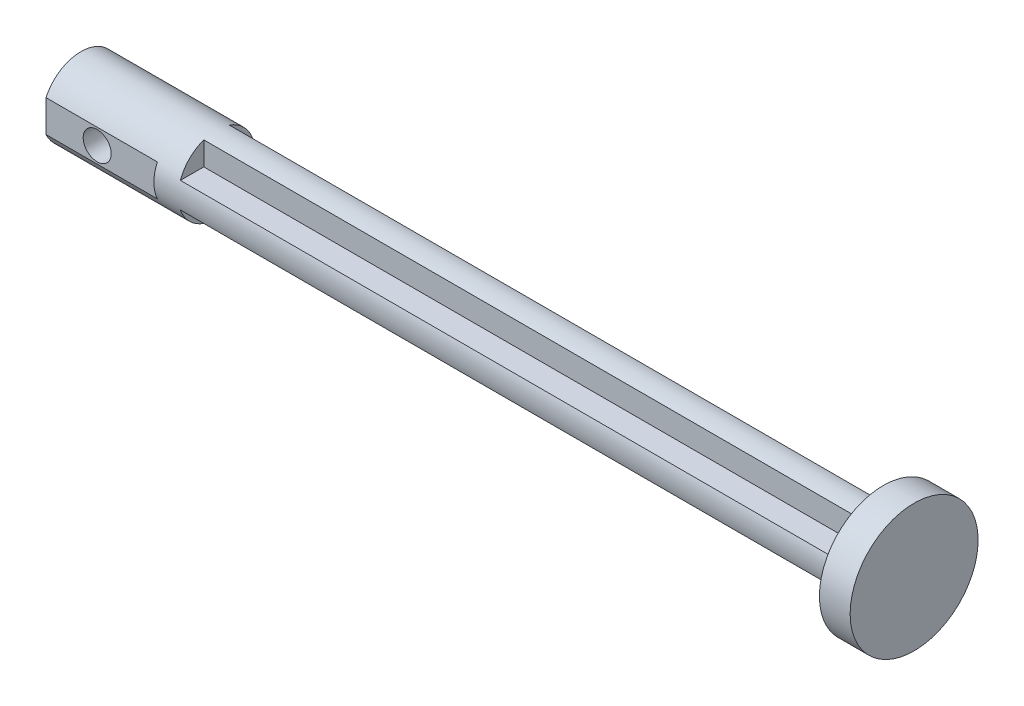
SolidWorks part; units mm, degrees
ref_plane "Front" through (0, 0, 0) normal (0, 0, 1) x (1, 0, 0)
ref_plane "Top" through (0, 0, 0) normal (0, 1, 0) x (1, 0, 0)
ref_plane "Right" through (0, 0, 0) normal (1, 0, 0) x (0, 0, -1)
sketch "Sketch1" plane through (0, 0, 0) normal (1, 0, 0) x (0, 0, -1)
  circle A0 centre (0, 0) radius 3.81
  dimension "D1" = 7.62
extrude "Base-Extrude" add sketch "Sketch1" along normal blind 13.462
ref_plane "Plane5" through (79.629, 0, 0) normal (1, 0, 0) x (0, 0, -1)
sketch "Sketch2" plane through (13.462, 0, 0) normal (1, 0, 0) x (0, 0, -1)
  line L0 (1.27, -1.27) -> (-1.27, 1.27) construction
  line L1 (1.27, -3.5921) -> (1.27, -1.27)
  line L2 (1.27, 1.27) -> (-1.27, -1.27) construction
  line L3 (-1.27, 3.5921) -> (-1.27, 1.27)
  line L4 (3.5921, 1.27) -> (1.27, 1.27)
  line L6 (-3.5921, -1.27) -> (-1.27, -1.27)
  line L8 (-1.27, 1.27) -> (-3.5921, 1.27)
  line L9 (1.27, 1.27) -> (1.27, 3.5921)
  line L10 (-1.27, -1.27) -> (-1.27, -3.5921)
  line L11 (1.27, -1.27) -> (3.5921, -1.27)
  circle A0 centre (0, 0) radius 3.81 construction
  arc A1 (1.27, 3.5921) -> (-1.27, 3.5921) centre (0, 0) ccw
  arc A2 (-3.5921, 1.27) -> (-3.5921, -1.27) centre (0, 0) ccw
  arc A3 (-1.27, -3.5921) -> (1.27, -3.5921) centre (0, 0) ccw
  arc A4 (3.5921, -1.27) -> (3.5921, 1.27) centre (0, 0) ccw
  dimension "D1" = 2.54
extrude "Boss-Extrude4" add sketch "Sketch2" along normal up to surface (66.167 mm away) up to plane "Plane5"
sketch "Sketch3" plane through (79.629, 0, 0) normal (1, 0, 0) x (0, 0, -1)
  circle A0 centre (0, 0) radius 6.35
  dimension "D1" = 12.7
extrude "Boss-Extrude5" add sketch "Sketch3" along normal blind 3.048
sketch "Sketch4" plane through (0, 0, 0) normal (-1, 0, 0) x (0, 0, 1)
  line L0 (3.4635, 1.5875) -> (3.4635, -1.5875)
  circle A1 centre (0, 0) radius 3.81
  arc A2 (3.4635, -1.5875) -> (3.4635, 1.5875) centre (0, 0) ccw
  dimension "D2" = 3.175
  dimension "D1" = 0
extrude "Cut-Extrude1" cut sketch "Sketch4" against normal blind 11.049
sketch "Sketch5" plane through (0, 0, 3.4635) normal (0, 0, 1) x (1, 0, 0)
  line L0 (0, 3.81) -> (0, -3.81) construction
  circle A0 centre (5.08, 0) radius 1.3891
  dimension "D1" = 2.7781
  dimension "D2" = 5.08
extrude "Cut-Extrude2" cut sketch "Sketch5" against normal blind 3.81
